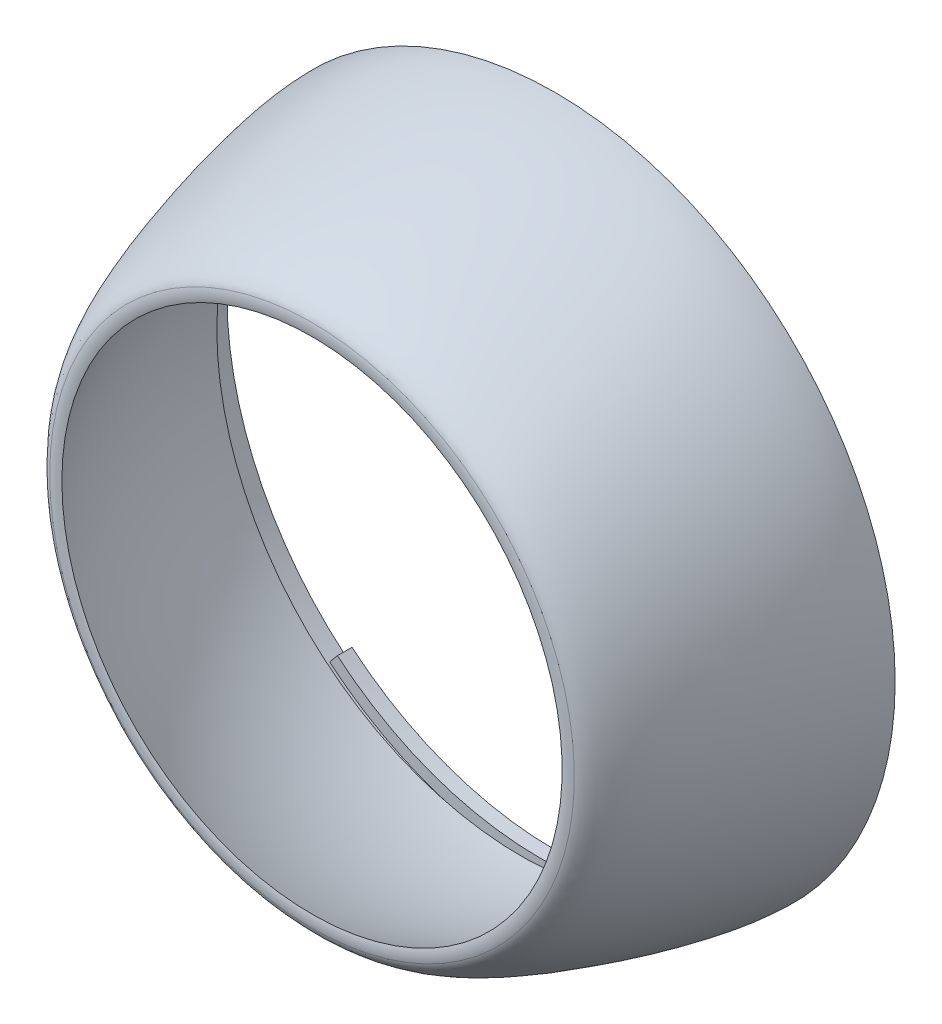
SolidWorks part; units mm, degrees
ref_plane "前视基准面" through (0, 0, 0) normal (0, 0, 1) x (1, 0, 0)
ref_plane "上视基准面" through (0, 0, 0) normal (0, 1, 0) x (1, 0, 0)
ref_plane "右视基准面" through (0, 0, 0) normal (1, 0, 0) x (0, 0, -1)
sketch "草图2" plane through (0, 0, 0) normal (1, 0, 0) x (0, 0, -1)
  line L0 (0, 28) -> (0, 25)
  line L1 (0, 0) -> (-10.599, 0) construction
  arc A0 (-20, 21.5897) -> (-20, 20.5897) centre (-18.2094, 21.0897) ccw
  spline S0 degree 2 poles (0, 25) (-10.5851, 25.4987) (-20, 20.5897) knots 0 0 0 1 1 1
  spline S1 degree 3 poles (0, 28) (-2.204, 28.03) (-10.1008, 26.5394) (-19.5532, 23.1896) (-20, 21.5897) knots 0 0 0 0 0.471702 1 1 1 1
  dimension "D1" = 1
  dimension "D2" = 2
  dimension "D3" = 3
  dimension "D4" = 10
  dimension "D5" = 0.7899
  dimension "D6" = 4.4103
  dimension "D7" = 20
  dimension "D8" = 25
revolve "旋转1" add sketch "草图2" angle 360 about L1
sketch "草图3" plane through (0, 0, 0) normal (0, 0, -1) x (-1, 0, 0)
  line L0 (0, 27) -> (0, 0)
  line L1 (0, 0) -> (-13.5, 23.3827)
  line L2 (0, 0) -> (-25.3717, -9.2345)
  line L3 (0, 0) -> (-9.2345, -25.3717)
  line L4 (17.3553, -20.6832) -> (0, 0)
  line L5 (0, 0) -> (25.3717, 9.2345)
  circle A0 centre (0, 0) radius 27 construction
  arc A2 (0, 27) -> (-13.5, 23.3827) centre (0, 0) ccw
  arc A3 (17.3553, -20.6832) -> (25.3717, 9.2345) centre (0, 0) ccw
  arc A4 (-25.3717, -9.2345) -> (-9.2345, -25.3717) centre (0, 0) ccw
  point P9 (-6.9881, 26.08)
  point P10 (-19.0919, -19.0919)
  point P11 (26.08, -6.9881)
  point P12 (-12.3747, 22.8663)
  point P13 (-3.2599, 25.7948)
  circle M2 centre (0, 0) radius 25
  dimension "D1" = 54
  dimension "D2" = 120
  dimension "D3" = 120
  dimension "D4" = 30
  dimension "D5" = 50
  dimension "D6" = 70
extrude "切除-拉伸5" cut sketch "草图3" against normal blind 1.2 contours L0 A2 L1 M2 | L1 L0 M2 | L3 L2 M2 | L2 A4 L3 M2 | L5 L4 M2 | L4 A3 L5 M2
sketch "草图4" plane through (0, 0, 1.2) normal (0, 0, -1) x (-1, 0, 0)
  circle A0 centre (0, 0) radius 27
  arc A1 (0, 27) -> (-13.5, 23.3827) centre (0, 0) ccw construction
extrude "切除-拉伸6" cut sketch "草图4" against normal blind 1.6
sketch "草图5" plane through (0, 0, 0) normal (0, 0, -1) x (-1, 0, 0)
  circle A0 centre (0, 0) radius 26
  dimension "D1" = 52
extrude "切除-拉伸7" cut sketch "草图5" against normal up to next
equation "\"涵道厚\"= 3mm"
equation "\"D3@草图2\"=\"涵道厚\""
equation "\"卡扣小缺口\" = 30度"
equation "\"卡扣中缺口\" = 50度"
equation "\"卡扣大缺口\"= 70度"
equation "\"卡扣半径\" = 54mm"
equation "\"D1@草图3\"=\"卡扣半径\""
equation "\"D4@草图3\"=\"卡扣小缺口\""
equation "\"D5@草图3\"=\"卡扣中缺口\""
equation "\"D6@草图3\"=\"卡扣大缺口\""
equation "\"卡扣厚度\"= 1.2mm"
equation "\"D1@切除-拉伸5\"=\"卡扣厚度\""
equation "\"卡扣空隙\"= 1.6mm"
equation "\"D1@切除-拉伸6\"=\"卡扣空隙\""
equation "\"卡扣壁半径\"= 52mm"
equation "\"D1@草图5\"=\"卡扣壁半径\""
